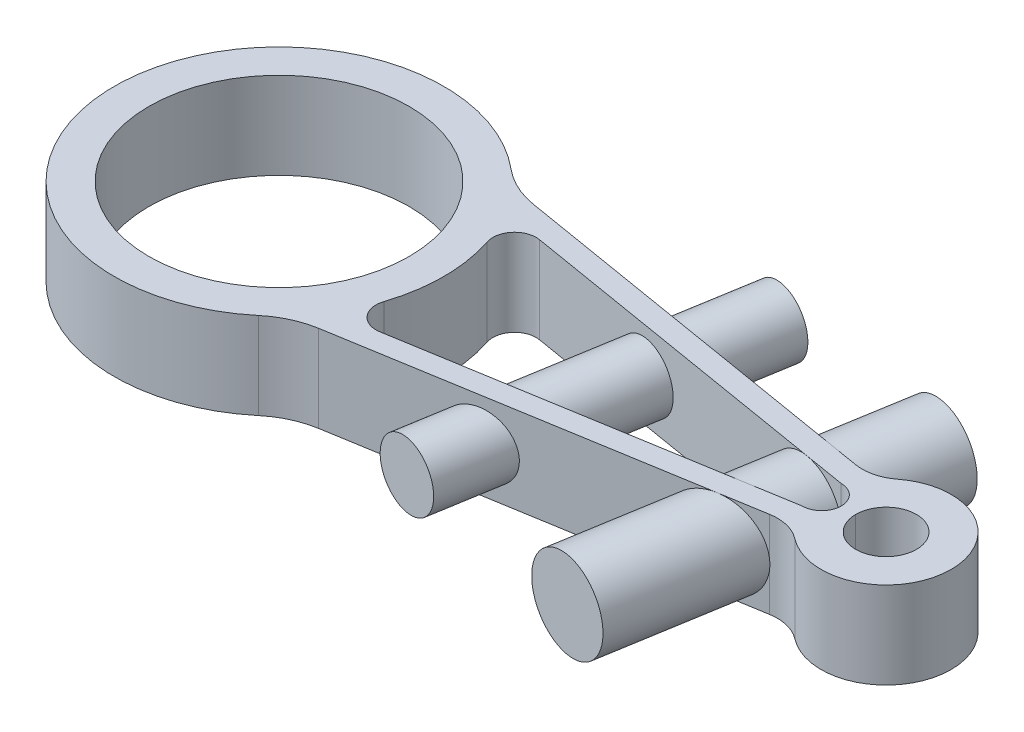
SolidWorks part; units mm, degrees
material "1023 Carbon Steel Sheet (SS)"
ref_plane "Front Plane" through (0, 0, 0) normal (0, 0, 1) x (1, 0, 0)
ref_plane "Top Plane" through (0, 0, 0) normal (0, 1, 0) x (1, 0, 0)
ref_plane "Right Plane" through (0, 0, 0) normal (1, 0, 0) x (0, 0, -1)
sketch "Sketch1" plane through (0, 0, 0) normal (0, 1, 0) x (1, 0, 0)
  line L0 (-77.078, 0) -> (170.6192, 0) construction
  line L1 (27.9355, -25.7606) -> (128.0638, -9.0844)
  line L2 (27.9355, 25.7606) -> (128.0638, 9.0844)
  circle A0 centre (0, 0) radius 30
  arc A1 (27.9355, 25.7606) -> (27.9355, -25.7606) centre (0, 0) ccw
  circle A2 centre (140, 0) radius 7
  arc A3 (128.0638, -9.0844) -> (128.0638, 9.0844) centre (140, 0) ccw
  dimension "D2" = 60
  dimension "D3" = 76
  dimension "D4" = 14
  dimension "D5" = 30
  dimension "D1" = 140
extrude "Boss-Extrude1" add sketch "Sketch1" along normal mid plane 20
fillet "Fillet1" radius 10 2 edges at (128.0638, 0, -9.0844) (128.0638, 0, 9.0844)
fillet "Fillet2" radius 20 2 edges at (27.9355, 0, 25.7606) (27.9355, 0, -25.7606)
sketch "Sketch2" plane through (0, 10, 0) normal (0, 1, 0) x (1, 0, 0)
  line L0 (0, 0) -> (155, 0) construction
  line L1 (41.6557, 18.4067) -> (125.1548, 4.5)
  line L2 (41.6557, -18.4067) -> (125.1548, -4.5)
  line L3 (33.9231, -24.7634) -> (123.0688, -9.9163) construction
  arc A0 (130.827, -11.8683) -> (130.827, 11.8683) centre (140, 0) ccw construction
  arc A1 (41.6557, 18.4067) -> (36.0861, 11.9078) centre (40.8342, 13.4746) ccw
  arc A2 (36.0861, -11.9078) -> (41.6557, -18.4067) centre (40.8342, -13.4746) ccw
  arc A3 (125.1548, -4.5) -> (125.1548, 4.5) centre (125.1548, 0) ccw
  circle A4 centre (0, 0) radius 30 construction
  arc A5 (36.0861, 11.9078) -> (36.0861, -11.9078) centre (0, 0) cw
  dimension "D1" = 10
  dimension "D2" = 8
  dimension "D4" = 4.5
  dimension "D3" = 5
extrude "Cut-Extrude1" cut sketch "Sketch2" against normal blind 10
mirror "Mirror1" about plane through (0, 0, 0) normal (0, 1, 0) of "Cut-Extrude1"
split line "Split Line1"
sketch "Sketch3" plane through (4.1071, 0, -24.6603) normal (-0.1643, 0, 0.9864) x (0.9864, 0, 0.1643)
  line L0 (0, 0) -> (136.1315, 0) construction
  line L1 (38.0657, -10) -> (38.0657, 10) construction
  circle A0 centre (113.0657, 0) radius 10
  circle A1 centre (68.0657, 0) radius 7.5
  dimension "D1" = 20
  dimension "D2" = 75
  dimension "D3" = 15
  dimension "D4" = 30
extrude "Boss-Extrude4" add sketch "Sketch3" along normal blind 48 and the other way blind 27 contours A0 | A1
